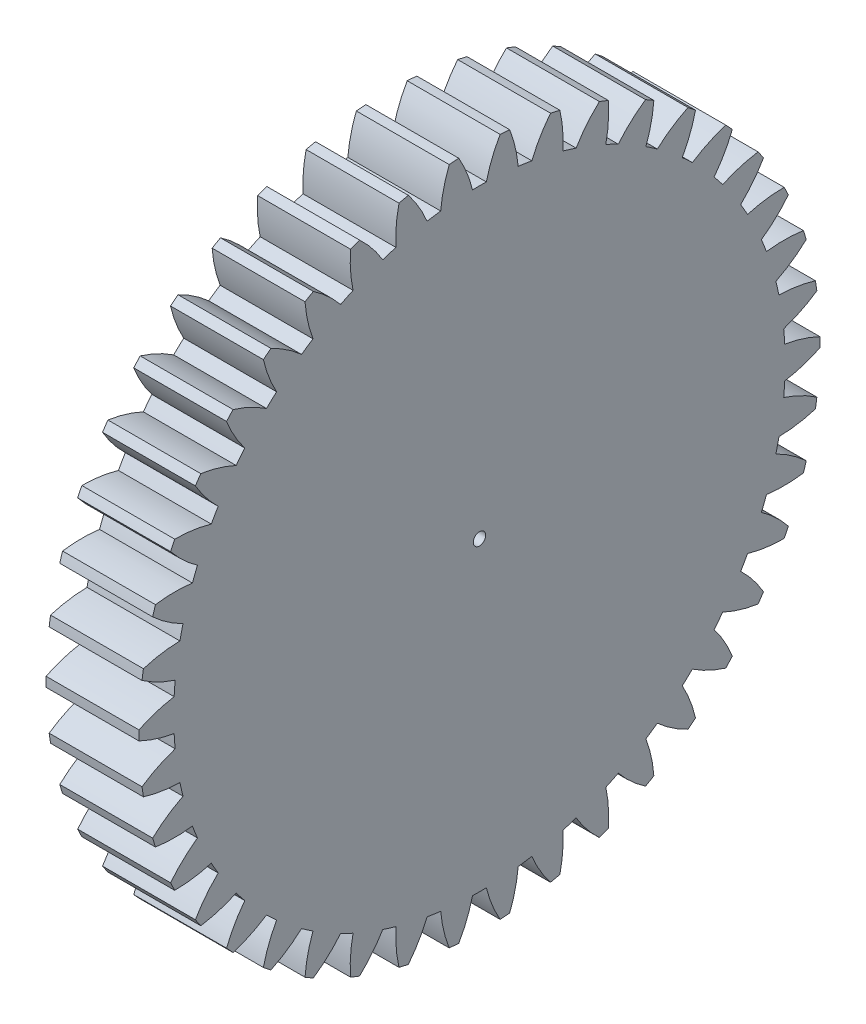
SolidWorks part; units mm, degrees
ref_plane "Plane1" through (0, 0, 0) normal (0, 0, 1) x (1, 0, 0)
ref_plane "Plane2" through (0, 0, 0) normal (0, 1, 0) x (1, 0, 0)
ref_plane "Plane3" through (0, 0, 0) normal (1, 0, 0) x (0, 0, -1)
other "Configuration Table"
sketch "HoldingSke" plane through (0, 0, 0) normal (0, 1, 0) x (1, 0, 0)
  line L0 (0, 0) -> (0.7431, -0.6691)
  line L1 (-15, 0) -> (100, 0) construction
  line L2 (0, 0) -> (-2.1039, 2.3779)
  line L3 (0, 0) -> (-11.863, 4.5341)
  line L4 (0, 0) -> (6.4178, 5.7786)
  line L5 (0, 0) -> (-46.8476, -17.4728)
  line L6 (0, 0) -> (-4.9738, -3.3558)
  line L7 (-2.1039, 2.3779) -> (8.6586, 51.2059)
  line L8 (-76.2, 54.61) -> (-76.1, 54.61)
  line L9 (-71.009, 38.7566) -> (-53.1078, 45.2721)
  line L10 (-76.2, 71.12) -> (104.1128, 71.12)
  line L11 (0, 0) -> (-6, 0)
  line L12 (-76.2, 101.6) -> (-76.162, 101.6)
  line L13 (24.9733, 27.94) -> (52.9518, 28.4284)
  line L14 (24.9733, 27.94) -> (24.9743, 27.94)
  line L15 (24.9733, 27.94) -> (100.4006, 29.5858)
  line L16 (-63.627, -1) -> (-12.827, -1)
  circle A0 centre (0, 0) radius 0.4
  circle A1 centre (0, 0) radius 19.749
  circle A2 centre (0, 0) radius 37.5
  circle A3 centre (0, 0) radius 0.4
  dimension "MHD" = 39.498
  dimension "Hub_dia" = 75
  dimension "Bore" = 0.8
  dimension "MBD" = 0.8
  dimension "Num_teeth" = 42
  dimension "Pitch" = 1
  dimension "Overall_len" = 50
  dimension "Show_teeth" = 42
  dimension "Thickness" = 6
  dimension "OAL" = 50.0001
  dimension "T_dim" = 0.1
  dimension "Ap" = 20
  dimension "H" = 19.05
  dimension "Pitch_radius" = 180.3128
  dimension "Width" = 6
  dimension "Backlash" = 0.038
  dimension "Addendum_fac" = 1
  dimension "Dedendum_fac" = 1.25
  dimension "Clearance_fac" = 0.25
  dimension "Dedendum_add" = 0.001
  dimension "Module" = 1
sketch "BasProSke" plane through (0, 0, 0) normal (0, 1, 0) x (1, 0, 0)
  line L0 (-10, 0) -> (60, 0) construction
  line L1 (0, 0) -> (0, 22)
  line L2 (0, 0) -> (6, 0)
  line L3 (6, 0) -> (6, 22)
  line L4 (6, 22) -> (0, 22)
  dimension "Thickness" = 6
  dimension "Diameter" = 44
revolve "Base-Revolve" add sketch "BasProSke" angle 360 about L0
sketch "TooCutSke" plane through (0, 0, 0) normal (1, 0, 0) x (0, 0, -1)
  line L1 (0, 0) -> (0, 107) construction
  line L2 (0, 0) -> (-0.8517, 20.9827) construction
  line L3 (0, 0) -> (-3.1368, 41.858) construction
  line L4 (-0.8517, 20.9827) -> (-1.5684, 20.929) construction
  arc A0 (0.4461, 19.744) -> (-0.4461, 19.744) centre (0, 0) ccw
  arc A1 (1.3487, 21.9841) -> (-1.3487, 21.9841) centre (0, 0) ccw
  circle A2 centre (0, 0) radius 21 construction
  circle A3 centre (0, 0) radius 19.7335 construction
  arc A4 (-0.4461, 19.744) -> (-1.3487, 21.9841) centre (-8.6078, 17.7572) ccw
  arc A5 (1.3487, 21.9841) -> (0.4461, 19.744) centre (8.6078, 17.7572) ccw
  dimension "Root_dia" = 39.498
  dimension "Overcut_dia" = 44.0508
  dimension "Pitch_dia" = 42
  dimension "Base_dia" = 39.4671
  dimension "Flank_rad" = 8.4
  dimension "Half_ang" = 4.286
  dimension "Half_CT" = 0.7187
extrude "ToothCut" cut sketch "TooCutSke" along normal through all
fillet "Breaks" [suppressed] radius 0.02
fillet "RootFillets" [suppressed] radius 0.251
pattern_circular "TeethCuts" count 42 every 8.571 about axis through (-10, 0, 0) along (1, 0, 0) of "ToothCut", "RootFillets", "Breaks"
sketch "HubNeaOneSke" plane through (0, 0, 0) normal (-1, 0, 0) x (0, 0, 1)
  circle A0 centre (0, 0) radius 19.749
  dimension "Diameter" = 39.498
extrude "HubNearOne" [suppressed] add sketch "HubNeaOneSke" along normal blind 44.0001
sketch "HubNeaBotSke" plane through (0, 0, 0) normal (-1, 0, 0) x (0, 0, 1)
  circle A0 centre (0, 0) radius 19.749
  dimension "Diameter" = 39.498
extrude "HubNearBoth" [suppressed] add sketch "HubNeaBotSke" along normal blind 22
ref_plane "FarPln" through (6, 0, 0) normal (1, 0, 0) x (0, 0, -1)
sketch "HubFarSke" plane through (6, 0, 0) normal (1, 0, 0) x (0, 0, -1)
  circle A0 centre (0, 0) radius 19.749
  dimension "Diameter" = 39.498
extrude "HubFar" [suppressed] add sketch "HubFarSke" along normal blind 22
sketch "BorSke" plane through (0, 0, 0) normal (1, 0, 0) x (0, 0, -1)
  circle A0 centre (0, 0) radius 0.4
  dimension "Diameter" = 0.8
extrude "Bore" cut sketch "BorSke" along normal mid plane 100.0001
sketch "KeySke" plane through (0, 0, 0) normal (1, 0, 0) x (0, 0, -1)
  line L0 (-0.05, 0) -> (-0.05, 0.5)
  line L1 (-0.05, 0.5) -> (0.05, 0.5)
  line L2 (0.05, 0.5) -> (0.05, 0)
  line L3 (0, 0) -> (0, 34) construction
  line L4 (-0.05, 0) -> (0.05, 0)
  dimension "Offset" = 0.5
  dimension "Width" = 0.1
extrude "Keyway" [suppressed] cut sketch "KeySke" along normal mid plane 100.0001
pattern_circular "Keyway2" [suppressed] count 2 every 90 about axis through (-10, 0, 0) along (1, 0, 0)
equation "' \"Module@HoldingSke\" = 6.35"
equation "' \"Num_teeth@HoldingSke\" = 12"
equation "' \"Ap@HoldingSke\" =  20"
equation "' \"Ap@HoldingSke\" = 20"
equation "' \"Width@HoldingSke\" = 0.5 * 25.4"
equation "' \"Hub_dia@HoldingSke\"= 1 * 25.4"
equation "' \"Hub_dia@HoldingSke\" = 1 * 25.4"
equation "' \"Overall_len@HoldingSke\" = 1.0 * 25.4"
equation "' \"Bore@HoldingSke\" = 0.75 * 25.4"
equation "' \"T_dim@HoldingSke\" = 0.1 * 25.4"
equation "' \"Width@KeySke\" = 0.25 * 25.4"
equation "' \"Show_teeth@HoldingSke\" = 13"
equation "' \"Backlash@HoldingSke\" = 0.009 * 25.4"
equation "' \"Addendum_fac@HoldingSke\" = 1.0"
equation "' \"Dedendum_fac@HoldingSke\" = 1.25"
equation "' \"Dedendum_add@HoldingSke\" = 0.00005 * 25.4"
equation "' \"Clearance_fac@HoldingSke\" = 0.25"
equation "\"Pitch@HoldingSke\" = 1 / \"Module@HoldingSke\""
equation "\"Overcut_dia@TooCutSke\" = (\"Num_teeth@HoldingSke\" + 2 * \"Addendum_fac@HoldingSke\") / \"Pitch@HoldingSke\" + 0.002 * 25.4"
equation "\"Pitch_dia@TooCutSke\" = \"Num_teeth@HoldingSke\" / \"Pitch@HoldingSke\""
equation "\"Base_dia@TooCutSke\" = \"Num_teeth@HoldingSke\" / \"Pitch@HoldingSke\" * cos((\"Ap@HoldingSke\"  * 3.14159265 / 180))"
equation "\"Root_dia@TooCutSke\" = (\"Num_teeth@HoldingSke\" + 2) / \"Pitch@HoldingSke\" - 2 * (\"Addendum_fac@HoldingSke\" + \"Dedendum_fac@HoldingSke\") / \"Pitch@HoldingSke\" - \"Dedendum_add@HoldingSke\" * 2"
equation "\"Half_ang@TooCutSke\" = 180 / \"Num_teeth@HoldingSke\""
equation "\"Half_CT@TooCutSke\" = \"Num_teeth@HoldingSke\" / \"Pitch@HoldingSke\" * sin((3.14159265 / 2 / \"Num_teeth@HoldingSke\")) / 2 - 7 * \"Backlash@HoldingSke\" / 4"
equation "\"Flank_rad@TooCutSke\" = \"Num_teeth@HoldingSke\" / \"Pitch@HoldingSke\" / 5"
equation "\"Radius@RootFillets\" = \"Clearance_fac@HoldingSke\" / \"Pitch@HoldingSke\" + \"Dedendum_add@HoldingSke\""
equation "\"Break_rad@Breaks\" = 0.02 / \"Pitch@HoldingSke\""
equation "\"Thickness@HoldingSke\" = \"Width@HoldingSke\""
equation "\"OAL@HoldingSke\" = \"Thickness@HoldingSke\""
equation "\"MHD@HoldingSke\" = (\"Num_teeth@HoldingSke\" + 2) / \"Pitch@HoldingSke\" - 2 * (\"Addendum_fac@HoldingSke\" + \"Dedendum_fac@HoldingSke\")  / \"Pitch@HoldingSke\" - \"Dedendum_add@HoldingSke\" * 2"
equation "\"MBD@HoldingSke\" = (\"Num_teeth@HoldingSke\" + 2) / \"Pitch@HoldingSke\" - 2 * (\"Addendum_fac@HoldingSke\" + \"Dedendum_fac@HoldingSke\")  / \"Pitch@HoldingSke\" - \"Dedendum_add@HoldingSke\" * 2 - 0.002 * 25.4"
equation "\"MHD@HoldingSke\" = ((sgn( \"MHD@HoldingSke\" - \"Hub_dia@HoldingSke\" )-1)*( \"MHD@HoldingSke\" - \"Hub_dia@HoldingSke\" ))/-2+ \"Hub_dia@HoldingSke\""
equation "\"MBD@HoldingSke\" = ((sgn( \"MBD@HoldingSke\" - \"Bore@HoldingSke\" )-1)*( \"MBD@HoldingSke\" - \"Bore@HoldingSke\" ))/-2+ \"Bore@HoldingSke\""
equation "\"OAL@HoldingSke\" = ((sgn( \"OAL@HoldingSke\" - \"Overall_len@HoldingSke\" )+1)*( \"OAL@HoldingSke\" - \"Overall_len@HoldingSke\" ))/2 + \"Overall_len@HoldingSke\" + 0.000002 * 25.4"
equation "\"Num_teeth@TeethCuts\" = int( \"Show_teeth@HoldingSke\" ) + 1"
equation "\"Num_teeth@TeethCuts\" = ((sgn( \"Num_teeth@TeethCuts\" - \"Num_teeth@HoldingSke\" )-1)*( \"Num_teeth@TeethCuts\" - \"Num_teeth@HoldingSke\" ))/-2+ \"Num_teeth@HoldingSke\""
equation "\"Num_teeth@TeethCuts\" = ((sgn( \"Num_teeth@TeethCuts\" - 2.0)+1)*( \"Num_teeth@TeethCuts\" - 2.0))/2 +2.0"
equation "\"Angle@TeethCuts\" = 360.0 / \"Num_teeth@HoldingSke\""
equation "\"Diameter@BasProSke\" = (\"Num_teeth@HoldingSke\" + 2 * \"Addendum_fac@HoldingSke\") / \"Pitch@HoldingSke\""
equation "\"Thickness@BasProSke\"  = \"Thickness@HoldingSke\""
equation "' \"Fillet_rad@BasProSke\" =  \"Thickness@HoldingSke\" * 0.05"
equation "' \"Fillet_rad@BasProSke\" = \"Thickness@HoldingSke\" * 0.05"
equation "\"MHD@HoldingSke\" = ((sgn( \"MHD@HoldingSke\" - \"Root_dia@TooCutSke\" )-1)*( \"MHD@HoldingSke\" - \"Root_dia@TooCutSke\" ))/-2+ \"Root_dia@TooCutSke\""
equation "\"Diameter@HubNeaOneSke\" = \"MHD@HoldingSke\""
equation "\"Length@HubNearOne\" = \"OAL@HoldingSke\" - \"Thickness@BasProSke\""
equation "\"Diameter@HubNeaBotSke\" = \"MHD@HoldingSke\""
equation "\"Length@HubNearBoth\" = ( \"OAL@HoldingSke\" - \"Thickness@BasProSke\" ) / 2.0"
equation "\"Thickness@FarPln\" = \"Thickness@BasProSke\""
equation "\"Diameter@HubFarSke\" = \"MHD@HoldingSke\""
equation "\"Length@HubFar\" = ( \"OAL@HoldingSke\" - \"Thickness@BasProSke\" ) / 2.0"
equation "\"Diameter@BorSke\" = \"MBD@HoldingSke\""
equation "\"D1@Bore\" = \"OAL@HoldingSke\" * 2.0"
equation "\"D1@Keyway\" = \"OAL@HoldingSke\" * 2.0"
equation "\"Offset@KeySke\" = \"T_dim@HoldingSke\" + \"MBD@HoldingSke\" / 2.0"
